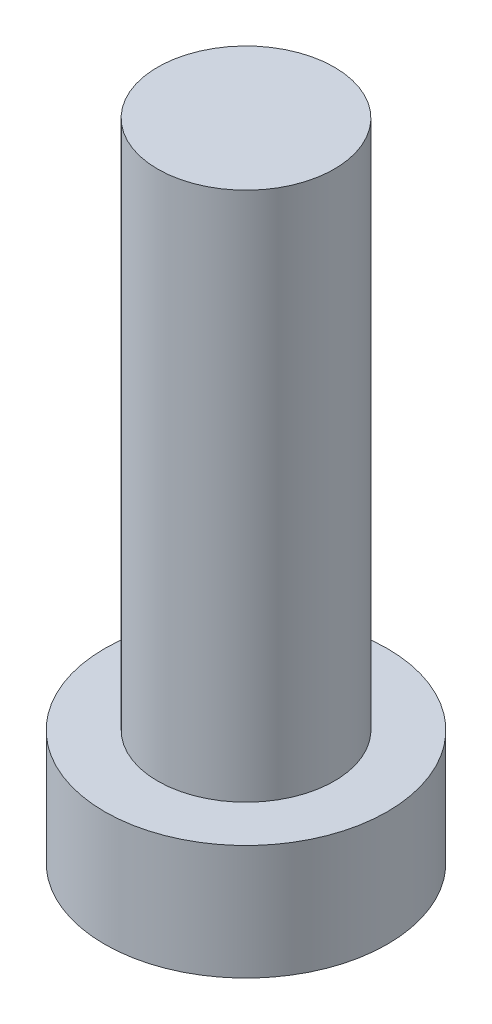
SolidWorks part; units mm, degrees
ref_plane "前视基准面" through (0, 0, 0) normal (0, 0, 1) x (1, 0, 0)
ref_plane "上视基准面" through (0, 0, 0) normal (0, 1, 0) x (1, 0, 0)
ref_plane "右视基准面" through (0, 0, 0) normal (1, 0, 0) x (0, 0, -1)
other "Configuration Table"
sketch "草图1" plane through (0, 0, 0) normal (0, 1, 0) x (1, 0, 0)
  circle A0 centre (0, 0) radius 1.6
  dimension "D1" = 3.2
extrude "凸台-拉伸1" add sketch "草图1" along normal blind 1.3
sketch "草图2" plane through (0, 0, 0) normal (0, 1, 0) x (1, 0, 0)
  circle A0 centre (0, 0) radius 1
extrude "凸台-拉伸2" add sketch "草图2" along normal blind 6 from surface at 1.3 starting at face at (0, 1.3, 1.6)
